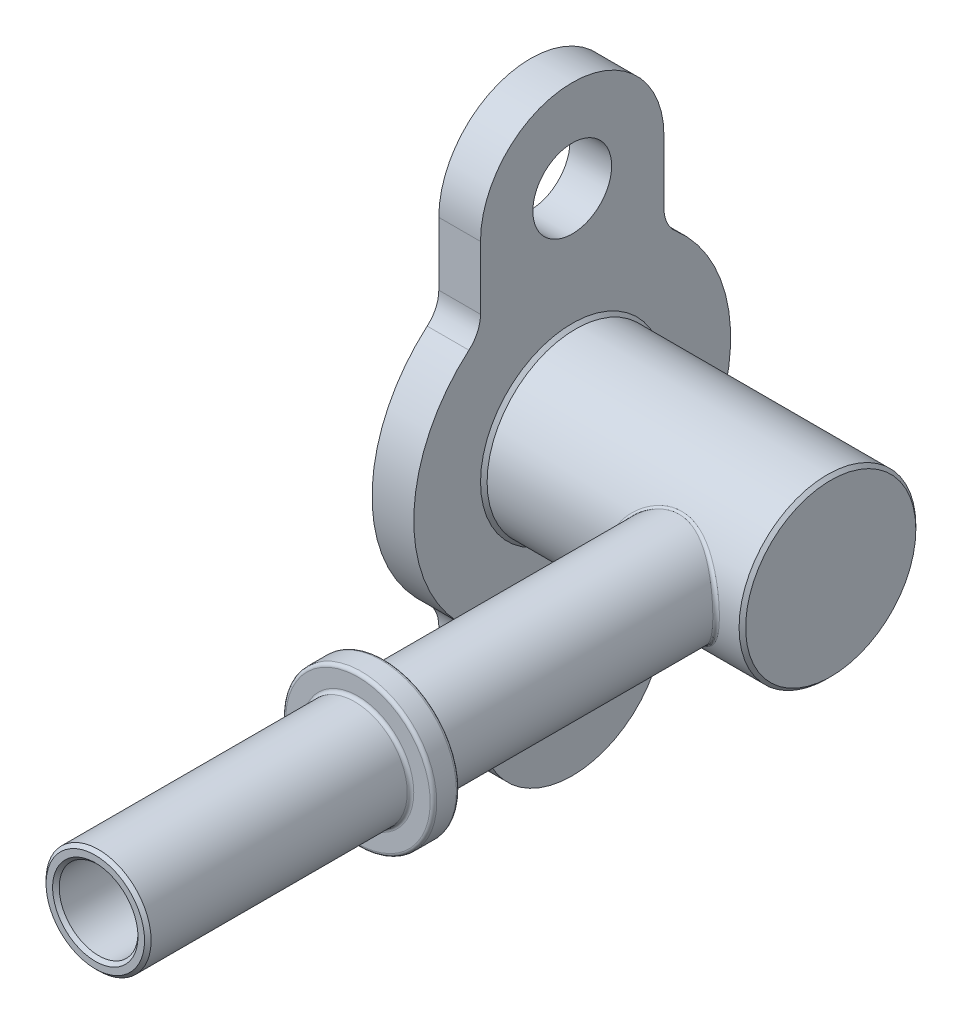
SolidWorks part; units mm, degrees
ref_plane "Front" through (0, 0, 0) normal (0, 0, 1) x (1, 0, 0)
ref_plane "Top" through (0, 0, 0) normal (0, 1, 0) x (1, 0, 0)
ref_plane "Right" through (0, 0, 0) normal (1, 0, 0) x (0, 0, -1)
sketch "Sketch1" plane through (0, 0, 0) normal (1, 0, 0) x (0, 0, -1)
  line L0 (0, -15.875) -> (0, 15.875) construction
  line L1 (-6.985, -15.875) -> (-6.985, -9.8374)
  line L2 (6.985, -15.875) -> (6.985, -9.8374)
  line L3 (-6.985, 15.875) -> (-6.985, 9.8374)
  line L4 (6.985, 15.875) -> (6.985, 9.8374)
  circle A0 centre (0, 0) radius 12.065 construction
  circle A1 centre (0, 15.875) radius 3
  circle A2 centre (0, -15.875) radius 3
  arc A3 (-6.985, 15.875) -> (6.985, 15.875) centre (0, 15.875) cw
  arc A4 (-6.985, -15.875) -> (6.985, -15.875) centre (0, -15.875) ccw
  arc A5 (6.985, 9.8374) -> (6.985, -9.8374) centre (0, 0) cw
  arc A6 (-6.985, 9.8374) -> (-6.985, -9.8374) centre (0, 0) ccw
  dimension "D1" = 24.13
  dimension "D2" = 6
  dimension "D3" = 6
  dimension "D6" = 6.985
  dimension "D7" = 6.985
  dimension "D4" = 31.75
  dimension "D5" = 15.875
extrude "Extrude1" add sketch "Sketch1" along normal blind 3.175
sketch "Sketch2" plane through (3.175, 0, 0) normal (1, 0, 0) x (0, 0, -1)
  circle A0 centre (0, 0) radius 6.731
  dimension "D1" = 13.462
extrude "Extrude2" add sketch "Sketch2" along normal blind 19.685
sketch "Sketch4" plane through (0, 0, 0) normal (0, 0, 1) x (1, 0, 0)
  line L0 (22.86, -6.731) -> (22.86, 6.731) construction
  circle A0 centre (16.86, 0) radius 4
  circle A1 centre (16.86, 0) radius 3
  dimension "D1" = 8
  dimension "D3" = 6
  dimension "D2" = 6
extrude "Extrude3" add sketch "Sketch4" along normal blind 28
sketch "Sketch5" plane through (0, 0, 28) normal (0, 0, 1) x (1, 0, 0)
  circle A0 centre (16.86, 0) radius 3
  circle A1 centre (16.86, 0) radius 5.75
  dimension "D1" = 11.5
extrude "Extrude4" add sketch "Sketch5" along normal blind 2
sketch "Sketch6" plane through (0, 0, 30) normal (0, 0, 1) x (1, 0, 0)
  circle A0 centre (16.86, 0) radius 3
  circle A1 centre (16.86, 0) radius 4
  dimension "D1" = 8
  dimension "D2" = 6
extrude "Extrude5" add sketch "Sketch6" along normal blind 20
chamfer "Chamfer1" distance 0.25 angle 45 4 edges at (19.86, 0, 50) (20.86, 0, 50) (3.175, 0, 6.731) (22.86, 0, -6.731)
fillet "Fillet1" radius 0.25 5 edges at (22.61, 0, 28) (22.61, 0, 30) (13.0131, -1.0959, 6.6412) (20.86, 0, 28) (20.86, 0, 30)
fillet "Fillet2" radius 2.54 4 edges at (1.5875, 9.8374, -6.985) (1.5875, -9.8374, -6.985) (1.5875, -9.8374, 6.985) (1.5875, 9.8374, 6.985)
sketch "Sketch7" plane through (0, 0, 0) normal (-1, 0, 0) x (0, 0, 1)
  circle A0 centre (0, 0) radius 6.35
  dimension "D1" = 12.7
extrude "Cut-Extrude1" cut sketch "Sketch7" against normal blind 20.32
sketch "Sketch8" plane through (0, 0, 50) normal (0, 0, 1) x (1, 0, 0)
  circle A0 centre (16.86, 0) radius 3
  dimension "D1" = 6
extrude "Cut-Extrude2" cut sketch "Sketch8" against normal blind 45.72
